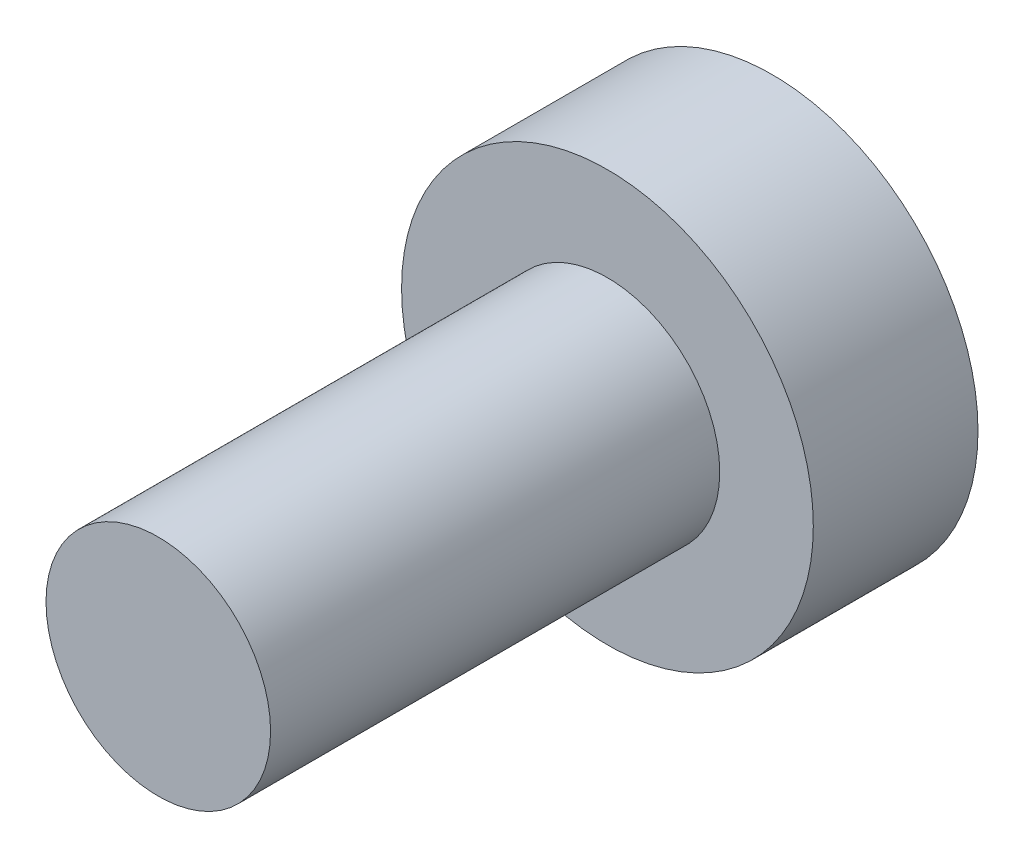
SolidWorks part; units mm, degrees
material "AISI 304"
ref_plane "前视基准面" through (0, 0, 0) normal (0, 0, 1) x (1, 0, 0)
ref_plane "上视基准面" through (0, 0, 0) normal (0, 1, 0) x (1, 0, 0)
ref_plane "右视基准面" through (0, 0, 0) normal (1, 0, 0) x (0, 0, -1)
sketch "草图1" plane through (0, 0, 0) normal (0, 0, 1) x (1, 0, 0)
  circle A0 centre (0, 0) radius 2.75
  dimension "D1" = 5.5
extrude "凸台-拉伸1" add sketch "草图1" along normal blind 2.2
sketch "草图2" plane through (0, 0, 2.2) normal (0, 0, 1) x (1, 0, 0)
  circle A0 centre (0, 0) radius 1.5
  dimension "D1" = 3
extrude "凸台-拉伸2" add sketch "草图2" along normal blind 6
